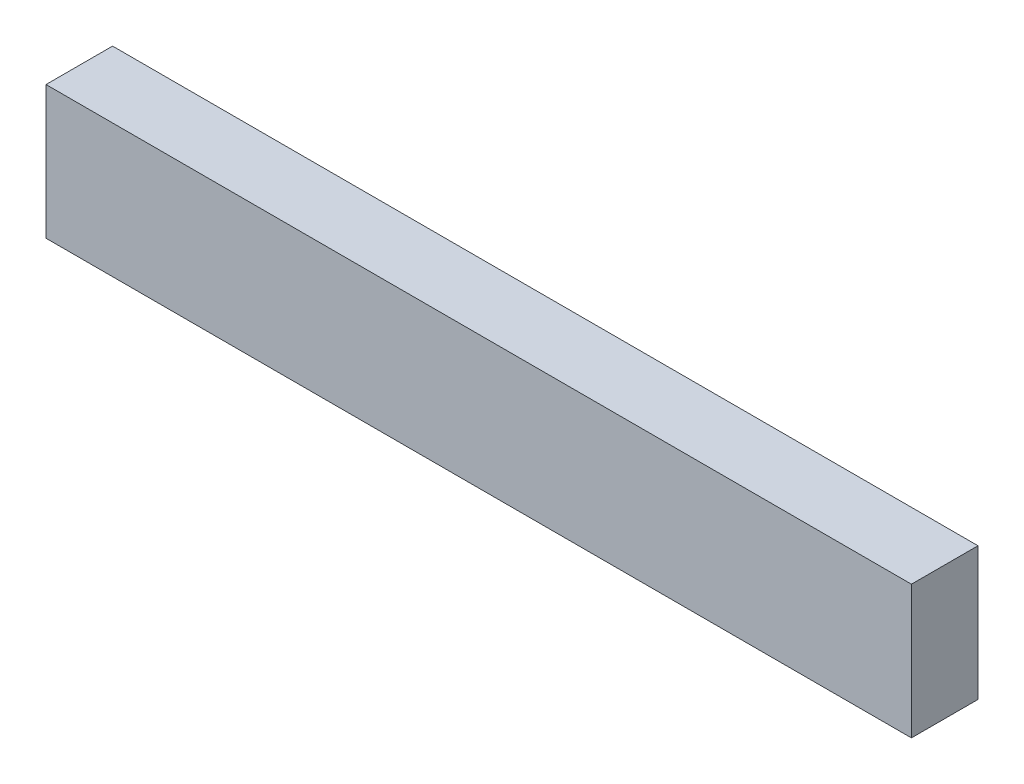
SolidWorks part; units mm, degrees
ref_plane "Front Plane" through (0, 0, 0) normal (0, 0, 1) x (1, 0, 0)
ref_plane "Top Plane" through (0, 0, 0) normal (0, 1, 0) x (1, 0, 0)
ref_plane "Right Plane" through (0, 0, 0) normal (1, 0, 0) x (0, 0, -1)
sketch "Sketch1" plane through (0, 0, 0) normal (1, 0, 0) x (0, 0, -1)
  line L1 (-6.35, 12.7) -> (6.35, 12.7)
  line L2 (-6.35, 12.7) -> (-6.35, -12.7)
  line L3 (-6.35, -12.7) -> (6.35, -12.7)
  line L4 (6.35, 12.7) -> (6.35, -12.7)
  line L5 (-6.35, 12.7) -> (6.35, -12.7) construction
  line L6 (-6.35, -12.7) -> (6.35, 12.7) construction
  point P0 (0, 0)
  dimension "D1" = 25.4
  dimension "D2" = 12.7
extrude "Boss-Extrude1" add sketch "Sketch1" along normal mid plane 165.1
